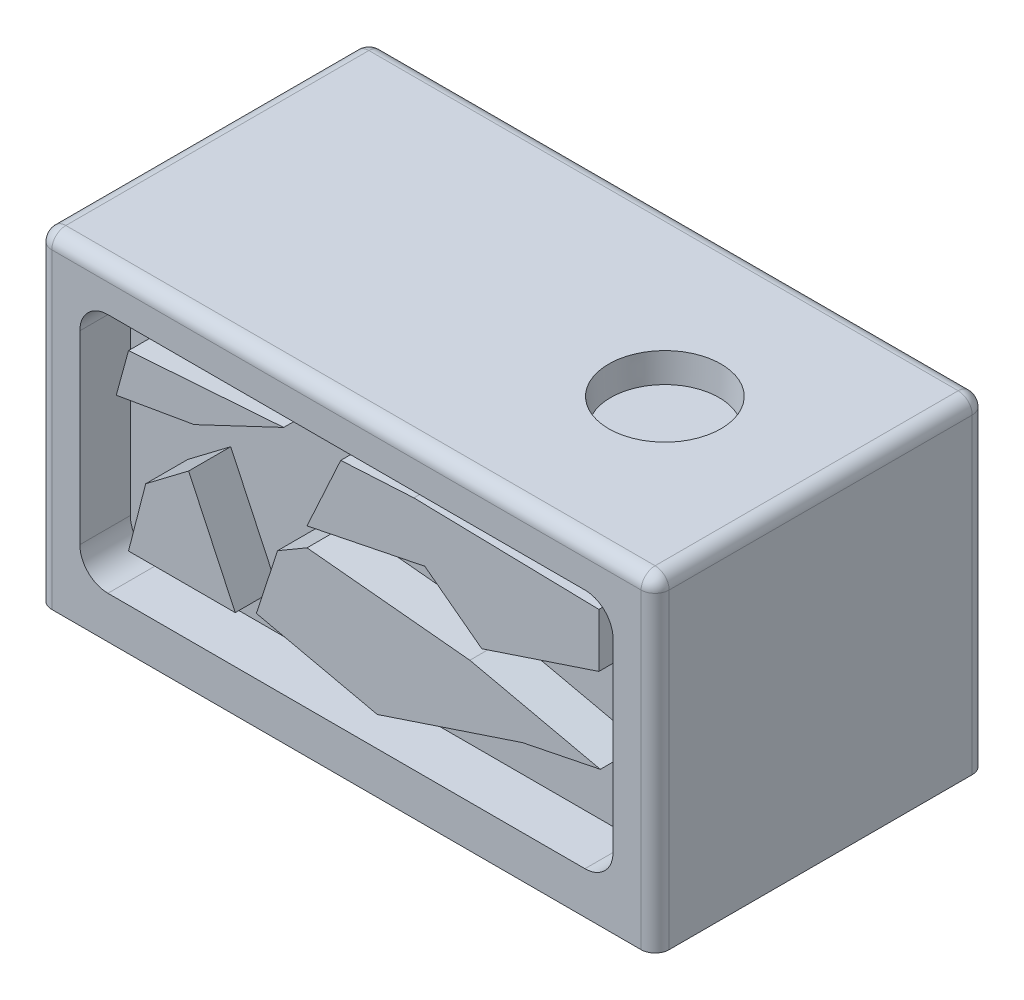
SolidWorks part; units mm, degrees
ref_plane "Front Plane" through (0, 0, 0) normal (0, 0, 1) x (1, 0, 0)
ref_plane "Top Plane" through (0, 0, 0) normal (0, 1, 0) x (1, 0, 0)
ref_plane "Right Plane" through (0, 0, 0) normal (1, 0, 0) x (0, 0, -1)
sketch "Sketch1" plane through (0, 0, 0) normal (0, 1, 0) x (1, 0, 0)
  line L1 (-90.015, 32.5394) -> (129.985, 32.5394)
  line L2 (-90.015, 32.5394) -> (-90.015, -67.4606)
  line L3 (-90.015, -67.4606) -> (129.985, -67.4606)
  line L4 (129.985, 32.5394) -> (129.985, -67.4606)
  line L5 (-72.015, 14.5394) -> (111.985, 14.5394)
  line L6 (-72.015, 14.5394) -> (-72.015, -49.4606)
  line L7 (-72.015, -49.4606) -> (111.985, -49.4606)
  line L8 (111.985, 14.5394) -> (111.985, -49.4606)
  dimension "D1" = 100
  dimension "D2" = 220
  dimension "D3" = 18
  dimension "D4" = 18
  dimension "D5" = 18
  dimension "D6" = 18
extrude "Boss-Extrude1" add sketch "Sketch1" along normal blind 80
sketch "Sketch11" plane through (0, 80, 0) normal (0, 1, 0) x (1, 0, 0)
  line L1 (-90.015, 32.5394) -> (129.985, 32.5394)
  line L2 (-90.015, 32.5394) -> (-90.015, -67.4606)
  line L3 (-90.015, -67.4606) -> (129.985, -67.4606)
  line L4 (129.985, 32.5394) -> (129.985, -67.4606)
extrude "Boss-Extrude6" add sketch "Sketch11" along normal blind 18
sketch "Sketch12" plane through (0, 0, 0) normal (0, -1, 0) x (1, 0, 0)
  line L1 (-90.015, 67.4606) -> (129.985, 67.4606)
  line L2 (-90.015, 67.4606) -> (-90.015, -32.5394)
  line L3 (-90.015, -32.5394) -> (129.985, -32.5394)
  line L4 (129.985, 67.4606) -> (129.985, -32.5394)
extrude "Boss-Extrude7" add sketch "Sketch12" along normal blind 18
sketch "Sketch2" plane through (0, 0, 67.4606) normal (0, 0, 1) x (1, 0, 0)
  line L13 (-90.015, 98) -> (129.985, 98)
  line L14 (-90.015, 98) -> (-90.015, -18)
  line L15 (-90.015, -18) -> (129.985, -18)
  line L16 (129.985, 98) -> (129.985, -18)
  line L17 (-90.015, 98) -> (129.985, 98)
  line L18 (-90.015, 98) -> (-90.015, -18)
  line L19 (-90.015, -18) -> (129.985, -18)
  line L20 (129.985, 98) -> (129.985, -18)
  line L21 (-75.015, 83) -> (114.985, 83)
  line L22 (-75.015, 83) -> (-75.015, -3)
  line L23 (-75.015, -3) -> (114.985, -3)
  line L24 (114.985, 83) -> (114.985, -3)
  dimension "D1" = 15
  dimension "D2" = 15
  dimension "D3" = 15
  dimension "D4" = 15
extrude "Boss-Extrude2" add sketch "Sketch2" along normal blind 18
sketch "Sketch3" plane through (0, 0, 67.4606) normal (0, 0, 1) x (1, 0, 0)
  line L0 (14.9579, 76.5012) -> (2.9366, 50.2728)
  line L5 (2.9366, 50.2728) -> (44.902, 58.797)
  line L6 (44.902, 58.797) -> (65.229, 43.4971)
  line L7 (-60.6673, 72.5669) -> (-65.0387, 56.6113)
  line L8 (65.229, 43.4971) -> (98.4516, 54.5349)
  line L9 (-65.0387, 56.6113) -> (-37.2803, 61.4199)
  line L10 (-37.2803, 61.4199) -> (-5.3691, 76.5012)
  line L11 (-5.3691, 76.5012) -> (-60.6673, 72.5669)
  line L12 (98.4516, 54.5349) -> (106.9447, 57.3566)
  line L13 (106.9447, 57.3566) -> (106.9447, 76.5012)
  line L14 (106.9447, 76.5012) -> (41.0113, 77.9512)
  line L15 (41.0113, 77.9512) -> (14.9579, 76.5012)
  line L16 (-54.5473, 34.5358) -> (-39.2474, 46.12)
  line L17 (-39.2474, 46.12) -> (-22.6361, 10.7116)
  line L18 (-22.6361, 10.7116) -> (-60.6673, 10.7116)
  line L19 (-60.6673, 10.7116) -> (-54.5473, 34.5358)
  line L20 (-7.5548, 37.3772) -> (-15.1112, 14.2419)
  line L21 (-15.1112, 14.2419) -> (27.9846, 4.5917)
  line L22 (27.9846, 4.5917) -> (79.6853, 21.7685)
  line L23 (79.6853, 21.7685) -> (107.4632, 27.4109)
  line L24 (107.4632, 27.4109) -> (60.9592, 37.8243)
  line L25 (60.9592, 37.8243) -> (2.9366, 43.4971)
  line L26 (2.9366, 43.4971) -> (-7.5548, 37.3772)
extrude "Boss-Extrude3" add sketch "Sketch3" along normal blind 15
fillet "Fillet9" radius 5 8 edges at (-90.015, 98, 26.4606) (129.985, 98, 26.4606) (19.985, 98, -32.5394) (19.985, 98, 85.4606) (-90.015, 40, 85.4606) (129.985, 40, 85.4606) (-90.015, 40, -32.5394) (129.985, 40, -32.5394)
fillet "Fillet8" radius 10 4 edges at (-75.015, -3, 76.4606) (-75.015, 83, 76.4606) (114.985, -3, 76.4606) (114.985, 83, 76.4606)
sketch "Sketch13" plane through (0, -18, 0) normal (0, -1, 0) x (1, 0, 0)
  line L0 (19.985, 85.4606) -> (19.985, -32.5394) construction
  line L1 (-85.015, 85.4606) -> (124.985, 85.4606) construction
  line L2 (-85.015, -32.5394) -> (124.985, -32.5394) construction
  line L3 (-90.015, 26.4606) -> (129.985, 26.4606) construction
  line L4 (-90.015, 80.4606) -> (-90.015, -27.5394) construction
  line L5 (129.985, -27.5394) -> (129.985, 80.4606) construction
  circle A0 centre (-75.015, 70.4606) radius 5
  circle A1 centre (114.985, 70.4606) radius 5
  circle A2 centre (114.985, -17.5394) radius 5
  circle A3 centre (-75.015, -17.5394) radius 5
  dimension "D1" = 10
  dimension "D2" = 15
  dimension "D3" = 15
extrude "Boss-Extrude8" add sketch "Sketch13" along normal blind 10
sketch "Sketch14" plane through (-90.015, 0, 0) normal (-1, 0, 0) x (0, 0, 1)
  line L0 (-27.5394, 93) -> (-27.5394, -18) construction
  line L1 (18.4606, 51) -> (34.4606, 51)
  line L2 (18.4606, 51) -> (18.4606, 24)
  line L3 (18.4606, 24) -> (34.4606, 24)
  line L4 (34.4606, 51) -> (34.4606, 24)
  line L5 (80.4606, 93) -> (-27.5394, 93) construction
  point P6 (-27.5394, 37.5)
  point P7 (18.4606, 37.5)
  point P10 (26.4606, 93)
  point P11 (26.4606, 51)
  dimension "D1" = 27
  dimension "D2" = 16
extrude "Cut-Extrude1" cut sketch "Sketch14" against normal blind 10 draft 6
sketch "Sketch15" plane through (0, 98, 0) normal (0, 1, 0) x (1, 0, 0)
  line L0 (124.985, -80.4606) -> (124.985, 27.5394) construction
  circle A0 centre (74.4579, -26.4606) radius 20
  point P4 (124.985, -26.4606)
  dimension "D1" = 40
extrude "Cut-Extrude2" cut sketch "Sketch15" against normal blind 10 draft 4
sketch "Sketch17" plane through (0, -18, 0) normal (0, -1, 0) x (1, 0, 0)
  line L0 (-90.015, 80.4606) -> (-90.015, -27.5394) construction
  line L1 (-60.015, 46.4606) -> (-30.015, 46.4606)
  line L2 (-60.015, 46.4606) -> (-60.015, 6.4606)
  line L3 (-60.015, 6.4606) -> (-30.015, 6.4606)
  line L4 (-30.015, 46.4606) -> (-30.015, 6.4606)
  point P8 (-90.015, 26.4606)
  point P9 (-60.015, 26.4606)
  dimension "D3" = 30
  dimension "D1" = 30
  dimension "D2" = 40
extrude "Cut-Extrude3" cut sketch "Sketch17" against normal blind 10
